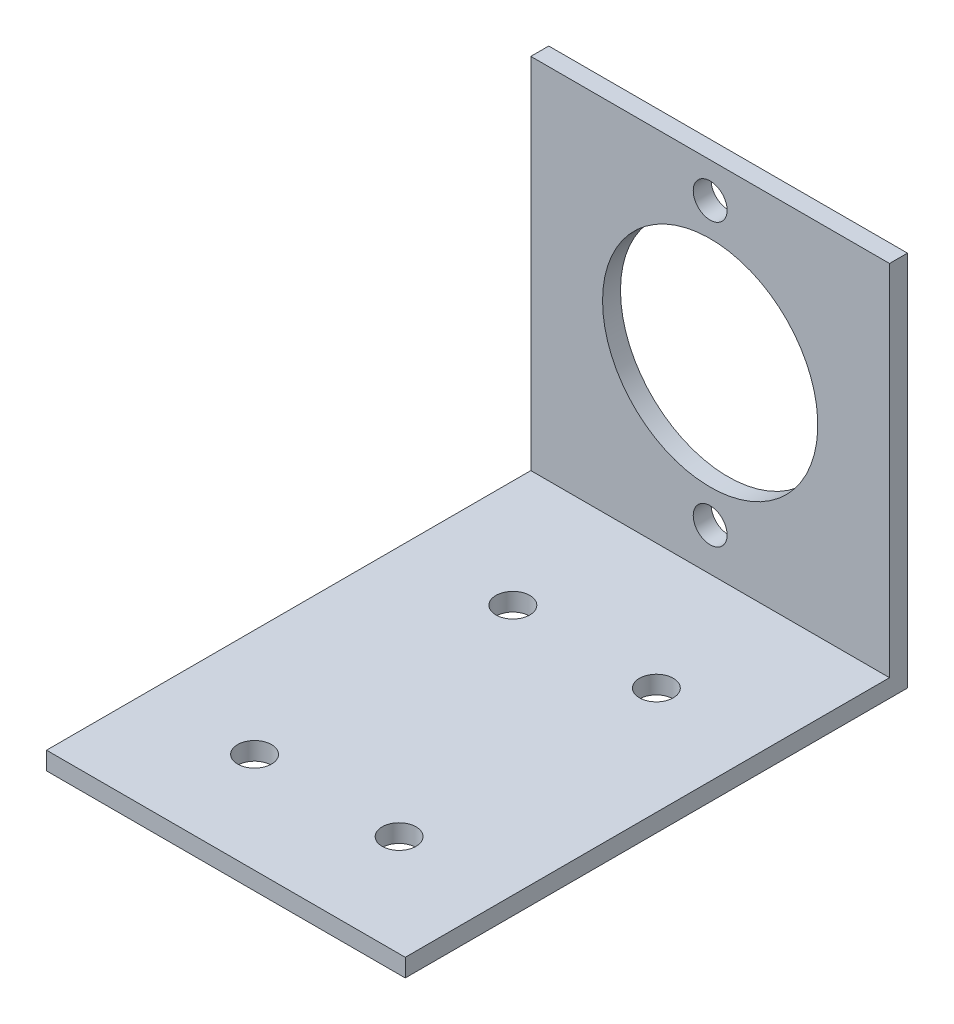
SolidWorks part; units mm, degrees
ref_plane "Front Plane" through (0, 0, 0) normal (0, 0, 1) x (1, 0, 0)
ref_plane "Top Plane" through (0, 0, 0) normal (0, 1, 0) x (1, 0, 0)
ref_plane "Right Plane" through (0, 0, 0) normal (1, 0, 0) x (0, 0, -1)
sketch "Sketch1" plane through (0, 0, 0) normal (0, 0, 1) x (1, 0, 0)
  line L1 (0, 0) -> (31.75, 0)
  line L2 (0, 0) -> (0, 1.5875)
  line L3 (0, 1.5875) -> (31.75, 1.5875)
  line L4 (31.75, 0) -> (31.75, 1.5875)
  dimension "D1" = 31.75
  dimension "D2" = 1.5875
extrude "Boss-Extrude1" add sketch "Sketch1" along normal blind 44.45
sketch "Sketch2" plane through (0, 1.5875, 0) normal (0, 1, 0) x (1, 0, 0)
  line L0 (9.525, -44.45) -> (9.525, 0) construction
  line L1 (31.75, -44.45) -> (0, -44.45) construction
  line L2 (31.75, 0) -> (0, 0) construction
  line L3 (22.225, 0) -> (22.225, -44.45) construction
  line L4 (31.75, -44.45) -> (31.75, 0) construction
  line L5 (0, 0) -> (31.75, 0)
  line L6 (0, 0) -> (0, -1.5875)
  line L7 (0, -1.5875) -> (31.75, -1.5875)
  line L8 (31.75, 0) -> (31.75, -1.5875)
  line L10 (0, -44.45) -> (0, 0) construction
  circle A0 centre (9.525, -12.7) radius 1.5875 construction
  circle A2 centre (9.525, -35.56) radius 1.5875 construction
  circle A3 centre (22.225, -35.4699) radius 1.5875 construction
  circle A5 centre (22.225, -12.7) radius 1.5875 construction
  dimension "D3" = 3.175
  dimension "D6" = 3.175
  dimension "D9" = 3.175
  dimension "D10" = 3.175
  dimension "D4" = 12.7
  dimension "D5" = 12.7
  dimension "D8" = 8.9801
  dimension "D11" = 8.89
  dimension "D12" = 1.5875
  dimension "D13" = 12.7
  dimension "D14" = 9.525
extrude "Boss-Extrude2" add sketch "Sketch2" along normal blind 31.75
sketch "Sketch3" plane through (0, 0, 0) normal (0, 0, -1) x (-1, 0, 0)
  line L0 (0, 0) -> (-31.75, 0) construction
  line L1 (-15.875, -0.1896) -> (-15.875, 35.7496)
  line L2 (-31.75, 0) -> (-31.75, 33.3375) construction
  circle A0 centre (-15.875, 17.78) radius 9.525
  point P7 (-15.875, 30.226)
  point P10 (-15.875, 17.78)
  point P11 (-15.875, 17.78)
  point P12 (-15.875, 5.334)
  point P16 (-32.385, 17.78)
  dimension "D3" = 19.05
  dimension "D1" = 17.78
  dimension "D2" = 15.875
  dimension "D4" = 12.446
  dimension "D5" = 12.446
  dimension "D9" = 16.51
extrude "Cut-Extrude1" cut sketch "Sketch3" against normal through all contours A0
hole_wizard "Ø3.0 (3) Diameter Hole1" positions "Sketch4" profile "Sketch5" hole size "Ø3.0" standard "ANSI Metric"
sketch "Sketch4" plane through (0, 0, 0) normal (0, 0, -1) x (-1, 0, 0)
  point P0 (-15.875, 30.226)
  point P3 (-15.875, 5.334)
sketch "Sketch5" plane through (15.875, 30.226, 0) normal (1, 0, 0) x (0, 1, 0)
  line L0 (0, 0) -> (0, 4.4573)
  line L1 (0, 4.4573) -> (1.5, 3.556)
  line L2 (1.5, 3.556) -> (1.5, 0)
  line L5 (1.5, 0) -> (0, 0)
  line L10 (0, 4.4573) -> (-1.5, 3.556) construction
  line L11 (0, -6.35) -> (0, 107.95) construction
  dimension "Hole Dia." = 3
  dimension "Hole Depth" = 3.556
  dimension "Drill Angle" = 118
hole_wizard "Ø3.0 (3) Diameter Hole2" positions "Sketch6" profile "Sketch7" hole size "Ø3.0" standard "ANSI Metric"
sketch "Sketch6" plane through (0, 1.5875, 0) normal (0, 1, 0) x (1, 0, 0)
  point P0 (22.225, -12.7)
  point P3 (22.225, -35.4699)
  point P6 (9.525, -12.7)
  point P9 (9.525, -35.56)
sketch "Sketch7" plane through (22.225, 1.5875, 12.7) normal (1, 0, 0) x (0, 0, 1)
  line L0 (0, 0) -> (0, 4.4573)
  line L1 (0, 4.4573) -> (1.5, 3.556)
  line L2 (1.5, 3.556) -> (1.5, 0)
  line L5 (1.5, 0) -> (0, 0)
  line L10 (0, 4.4573) -> (-1.5, 3.556) construction
  line L11 (0, -6.35) -> (0, 107.95) construction
  dimension "Hole Dia." = 3
  dimension "Hole Depth" = 3.556
  dimension "Drill Angle" = 118
